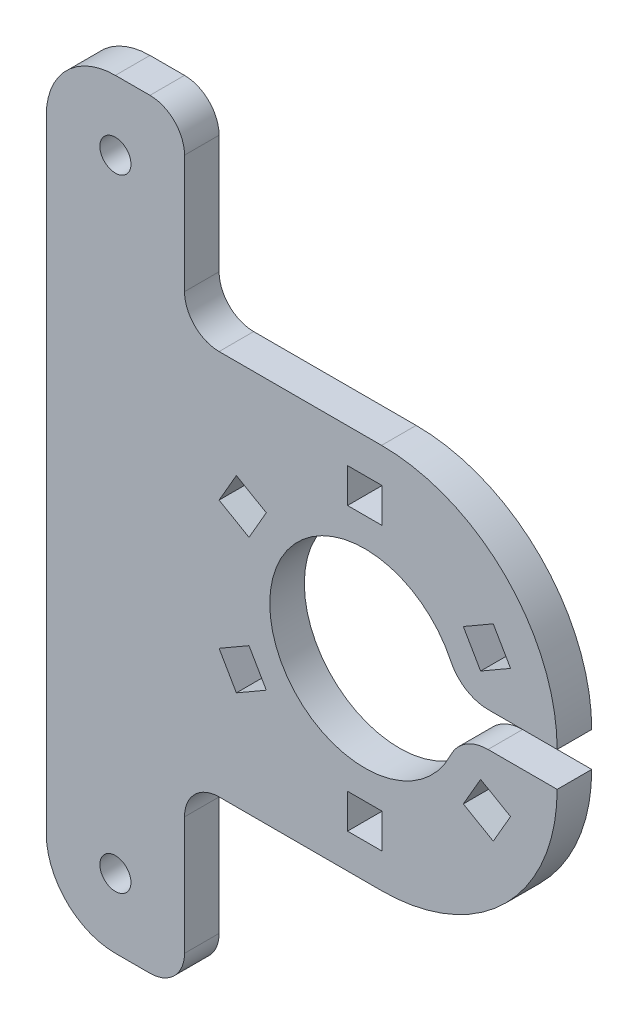
SolidWorks part; units mm, degrees
ref_plane "Plan de face" through (0, 0, 0) normal (0, 0, 1) x (1, 0, 0)
ref_plane "Plan de dessus" through (0, 0, 0) normal (0, 1, 0) x (1, 0, 0)
ref_plane "Plan de droite" through (0, 0, 0) normal (1, 0, 0) x (0, 0, -1)
sketch "Esquisse1" plane through (0, 0, 0) normal (0, 0, 1) x (1, 0, 0)
  line L0 (-58.9093, -55) -> (-63.9093, -55)
  line L1 (-73.9093, -45) -> (-73.9093, 45)
  line L2 (-63.9093, 55) -> (-58.9093, 55)
  line L3 (-53.9093, 50) -> (-53.9093, 32.9)
  line L4 (0, 2.5) -> (0, -2.5) construction
  line L5 (-48.9093, 27.9) -> (-25.4, 27.9)
  line L7 (-25.4, -27.9) -> (-48.9093, -27.9)
  line L8 (-53.9093, -32.9) -> (-53.9093, -50)
  line L17 (-60, 0) -> (0, 0) construction
  line L44 (-27.8273, 17.9) -> (-27.8273, 0) construction
  line L45 (-30.3273, 22.9) -> (-25.3273, 22.9)
  line L46 (-30.3273, 22.9) -> (-30.3273, 17.9)
  line L47 (-30.3273, 17.9) -> (-25.3273, 17.9)
  line L48 (-25.3273, 22.9) -> (-25.3273, 17.9)
  line L49 (-9.2453, 13.6151) -> (-6.7453, 9.2849)
  line L50 (-9.2453, 13.6151) -> (-13.5754, 11.1151)
  line L51 (-13.5754, 11.1151) -> (-11.0754, 6.7849)
  line L52 (-6.7453, 9.2849) -> (-11.0754, 6.7849)
  line L53 (-6.7453, -9.2849) -> (-9.2453, -13.6151)
  line L54 (-6.7453, -9.2849) -> (-11.0754, -6.7849)
  line L55 (-11.0754, -6.7849) -> (-13.5754, -11.1151)
  line L56 (-9.2453, -13.6151) -> (-13.5754, -11.1151)
  line L57 (-25.3273, -22.9) -> (-30.3273, -22.9)
  line L58 (-25.3273, -22.9) -> (-25.3273, -17.9)
  line L59 (-25.3273, -17.9) -> (-30.3273, -17.9)
  line L60 (-30.3273, -22.9) -> (-30.3273, -17.9)
  line L61 (-46.4093, -13.6151) -> (-48.9093, -9.2849)
  line L62 (-46.4093, -13.6151) -> (-42.0792, -11.1151)
  line L63 (-42.0792, -11.1151) -> (-44.5792, -6.7849)
  line L64 (-48.9093, -9.2849) -> (-44.5792, -6.7849)
  line L65 (-48.9093, 9.2849) -> (-46.4093, 13.6151)
  line L66 (-48.9093, 9.2849) -> (-44.5792, 6.7849)
  line L67 (-44.5792, 6.7849) -> (-42.0792, 11.1151)
  line L68 (-46.4093, 13.6151) -> (-42.0792, 11.1151)
  line L70 (0, 2.5) -> (-10, 2.5)
  line L71 (-10, -2.5) -> (0, -2.5)
  arc A0 (-25.4, 27.9) -> (0, 2.5) centre (-25.4, 2.5) cw
  arc A1 (-15.4159, 5.9177) -> (-15.4159, -5.9177) centre (-27.8273, 0) ccw
  arc A2 (-10, -2.5) -> (-15.4159, -5.9177) centre (-10, -8.5) ccw
  arc A3 (-10, 2.5) -> (-15.4159, 5.9177) centre (-10, 8.5) cw
  arc A4 (0, -2.5) -> (-25.4, -27.9) centre (-25.4, -2.5) cw
  arc A5 (-63.9093, -55) -> (-73.9093, -45) centre (-63.9093, -45) cw
  arc A6 (-73.9093, 45) -> (-63.9093, 55) centre (-63.9093, 45) cw
  arc A7 (-53.9093, -50) -> (-58.9093, -55) centre (-58.9093, -50) cw
  arc A8 (-53.9093, 50) -> (-58.9093, 55) centre (-58.9093, 50) ccw
  arc A9 (-48.9093, -27.9) -> (-53.9093, -32.9) centre (-48.9093, -32.9) ccw
  arc A10 (-53.9093, 32.9) -> (-48.9093, 27.9) centre (-48.9093, 32.9) ccw
  point P8 (-22.6506, -25.1506)
  point P10 (0, 0)
  point P15 (-73.9093, 55)
  point P18 (-23.81, 26.31)
  point P19 (-53.9093, 53.1166)
  point P23 (-53.9093, -55)
  point P26 (-53.9093, 55)
  point P31 (-53.9093, 27.9)
  point P82 (-27.8273, 0)
  dimension "D10" = 27.5
  dimension "D17" = 6
  dimension "D5" = 10
  dimension "D8" = 5
  dimension "D2" = 20
  dimension "D3" = 5
  dimension "D4" = 10
  dimension "D6" = 5
  dimension "D7" = 110
  dimension "D11" = 17.9
  dimension "D12" = 5
  dimension "D13" = 6
  dimension "D15" = 5
extrude "Boss.-Extru.1" add sketch "Esquisse1" along normal blind 5
hole_wizard "Dégagement M41" positions "Esquisse2" profile "Esquisse3" hole size "M4" standard "ISO" end condition through all
sketch "Esquisse2" plane through (0, 0, 5) normal (0, 0, 1) x (1, 0, 0)
  point P0 (-63.9093, 45)
  point P2 (-63.9093, -45)
sketch "Esquisse3" plane through (-63.9093, 45, 5) normal (1, 0, 0) x (0, -1, 0)
  line L0 (0, 0) -> (0, 5)
  line L1 (0, 5) -> (2.25, 5)
  line L2 (2.25, 5) -> (2.25, 0)
  line L5 (2.25, 0) -> (0, 0)
  line L11 (0, -6.35) -> (0, 107.95) construction
  dimension "Diamètre du perçage jusqu'au prochain" = 4.5
  dimension "Profondeur du perçage jusqu'au prochain" = 5
